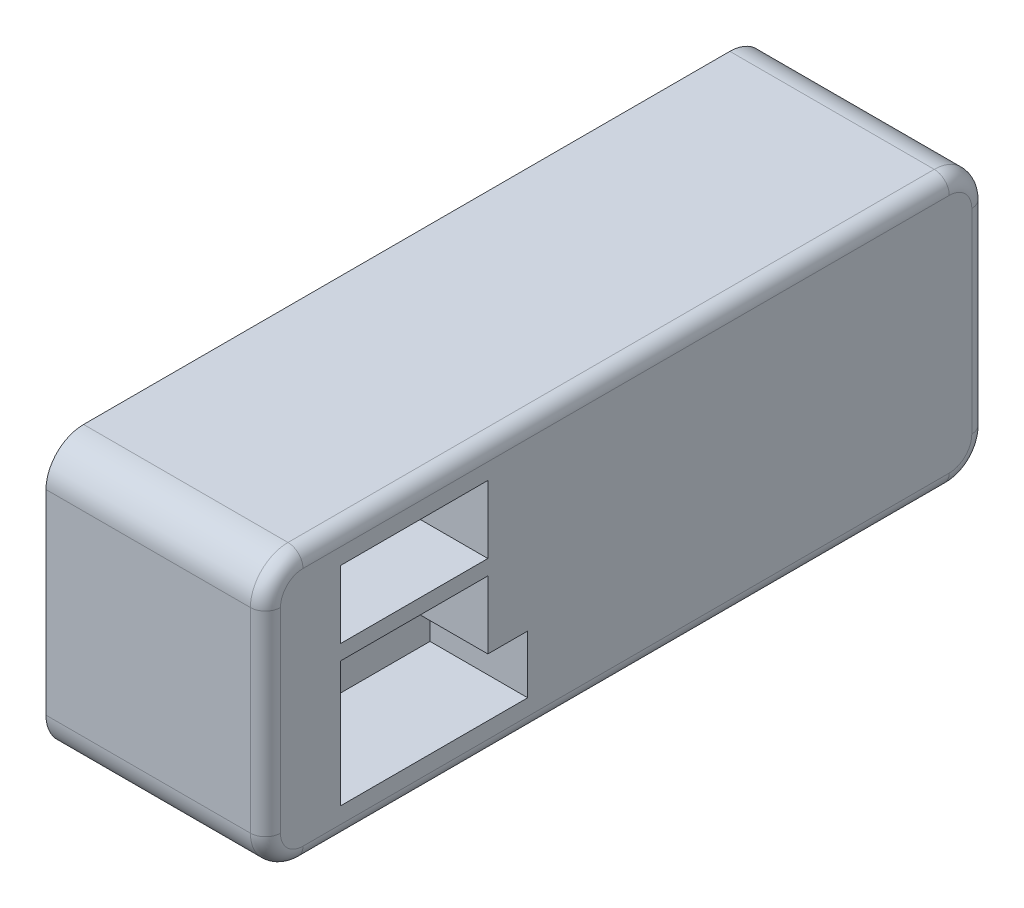
SolidWorks part; units mm, degrees
ref_plane "正面" through (0, 0, 0) normal (0, 0, 1) x (1, 0, 0)
ref_plane "平面" through (0, 0, 0) normal (0, 1, 0) x (1, 0, 0)
ref_plane "右側面" through (0, 0, 0) normal (1, 0, 0) x (0, 0, -1)
sketch "ｽｹｯﾁ1" plane through (0, 0, 0) normal (1, 0, 0) x (0, 0, -1)
  line L0 (-24, 0) -> (24, 0) construction
  line L1 (-21.5, 9) -> (21.5, 9)
  line L2 (-24, 6.5) -> (-24, -6.5)
  line L3 (-21.5, -9) -> (21.5, -9)
  line L4 (24, 6.5) -> (24, -6.5)
  arc A0 (21.5, 9) -> (24, 6.5) centre (21.5, 6.5) cw
  arc A1 (21.5, -9) -> (24, -6.5) centre (21.5, -6.5) ccw
  arc A2 (-24, -6.5) -> (-21.5, -9) centre (-21.5, -6.5) ccw
  arc A3 (-21.5, 9) -> (-24, 6.5) centre (-21.5, 6.5) ccw
  point P9 (24, 9)
  point P12 (24, -9)
  point P17 (-24, 9)
  dimension "D3" = 2.5
  dimension "D1" = 48
  dimension "D2" = 18
extrude "ﾎﾞｽ - 押し出し1" add sketch "ｽｹｯﾁ1" along normal blind 14.6
fillet "ﾌｨﾚｯﾄ1" radius 1 8 edges at (14.6, 0, -24) (14.6, -8.2678, -23.2678) (14.6, -9, 0) (14.6, -8.2678, 23.2678) (14.6, 0, 24) (14.6, 8.2678, 23.2678) (14.6, 9, 0) (14.6, 8.2678, -23.2678)
sketch "ｽｹｯﾁ2" plane through (0, 0, -24) normal (0, 0, -1) x (-1, 0, 0)
  line L0 (0, 0) -> (-8, 0) construction
  line L2 (-9.15, 3.433) -> (-8.25, 2.9134)
  line L3 (-9.9, 3) -> (-9.9, -3)
  line L4 (-9.15, -3.433) -> (-8.25, -2.9134)
  line L5 (-8, 2.4804) -> (-8, -2.4804)
  arc A0 (-8.25, -2.9134) -> (-8, -2.4804) centre (-8.5, -2.4804) ccw
  arc A1 (-9.9, -3) -> (-9.15, -3.433) centre (-9.4, -3) ccw
  arc A2 (-8.25, 2.9134) -> (-8, 2.4804) centre (-8.5, 2.4804) cw
  arc A3 (-9.15, 3.433) -> (-9.9, 3) centre (-9.4, 3) ccw
  dimension "D3" = 0.5
  dimension "D1" = 60
  dimension "D2" = 60
  dimension "D4" = 6
  dimension "D5" = 1.9
  dimension "D6" = 8
extrude "ｶｯﾄ - 押し出し1" cut sketch "ｽｹｯﾁ2" against normal blind 8
chamfer "面取り1" distance 0.5 angle 45 8 edges at (9.9, 0, -24) (9.65, -3.433, -24) (9.65, 3.433, -24) (8.7, -3.1732, -24) (8.7, 3.1732, -24) (8.067, -2.7304, -24) (8.067, 2.7304, -24) (8, 0, -24)
sketch "ｽｹｯﾁ3" plane through (14.6, 0, 0) normal (1, 0, 0) x (0, 0, -1)
  line L0 (-19, 1.425) -> (-19, -6.925)
  line L1 (-19, -6.925) -> (-6.55, -6.925)
  line L2 (-6.55, -6.925) -> (-6.55, -3.075)
  line L3 (-6.55, -3.075) -> (-9.2, -3.075)
  line L4 (-9.2, -3.075) -> (-9.2, 1.425)
  line L5 (-9.2, 1.425) -> (-19, 1.425)
  line L6 (0, 0) -> (6.5415, 0) construction
  line L7 (-19, 6.925) -> (-9.2, 6.925)
  line L8 (-19, 6.925) -> (-19, 2.425)
  line L9 (-19, 2.425) -> (-9.2, 2.425)
  line L10 (-9.2, 6.925) -> (-9.2, 2.425)
  line L11 (-24, -6.5) -> (-24, 6.5) construction
  dimension "D1" = 9.8
  dimension "D2" = 12.45
  dimension "D3" = 3.85
  dimension "D4" = 4.5
  dimension "D5" = 1
  dimension "D6" = 5
  dimension "D7" = 4.5
extrude "ｶｯﾄ - 押し出し2" cut sketch "ｽｹｯﾁ3" against normal blind 6.5
